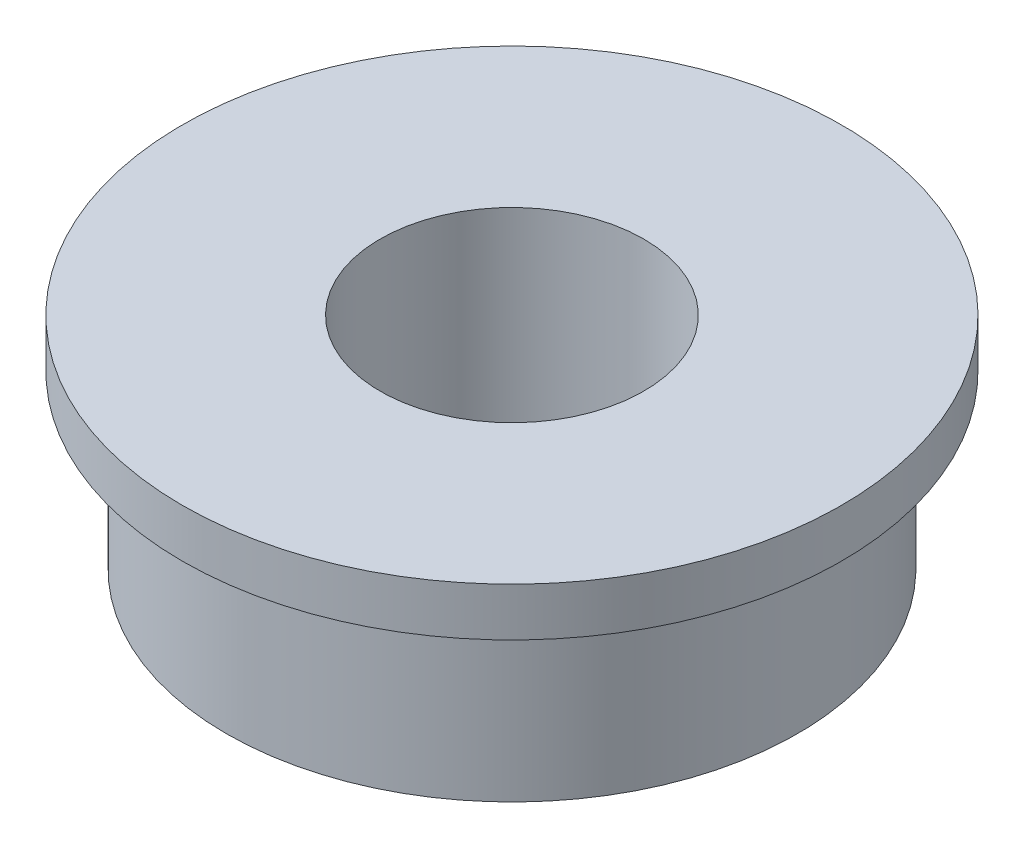
SolidWorks part; units mm, degrees
ref_plane "正面" through (0, 0, 0) normal (0, 0, 1) x (1, 0, 0)
ref_plane "平面" through (0, 0, 0) normal (0, 1, 0) x (1, 0, 0)
ref_plane "右側面" through (0, 0, 0) normal (1, 0, 0) x (0, 0, -1)
sketch "ｽｹｯﾁ1" plane through (0, 0, 0) normal (0, 1, 0) x (1, 0, 0)
  circle A0 centre (0, 0) radius 6.5
  dimension "D1" = 13
extrude "ﾎﾞｽ - 押し出し1" add sketch "ｽｹｯﾁ1" along normal mid plane 5
sketch "ｽｹｯﾁ2" plane through (0, 2.5, 0) normal (0, 1, 0) x (1, 0, 0)
  circle A0 centre (0, 0) radius 7.5
  dimension "D1" = 15
extrude "ﾎﾞｽ - 押し出し3" add sketch "ｽｹｯﾁ2" against normal blind 1.1
sketch "ｽｹｯﾁ6" plane through (0, -2.5, 0) normal (0, -1, 0) x (1, 0, 0)
  circle A0 centre (0, 0) radius 3
  dimension "D1" = 6
extrude "ｶｯﾄ - 押し出し3" cut sketch "ｽｹｯﾁ6" against normal through all
